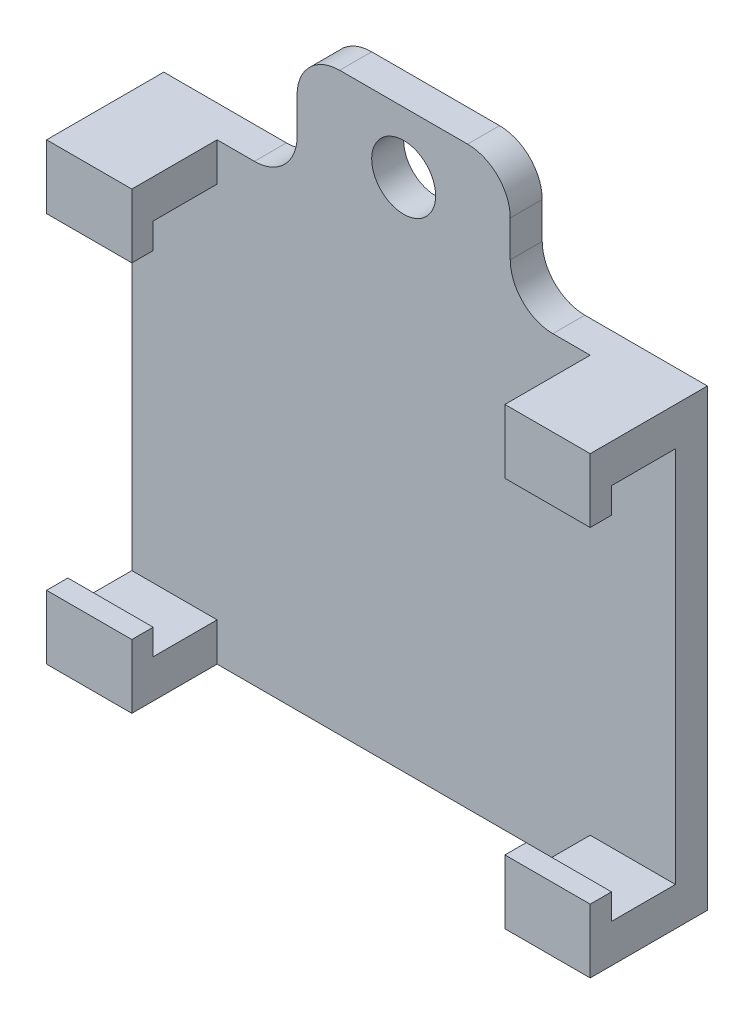
SolidWorks part; units mm, degrees
ref_plane "Front" through (0, 0, 0) normal (0, 0, 1) x (1, 0, 0)
ref_plane "Top" through (0, 0, 0) normal (0, 1, 0) x (1, 0, 0)
ref_plane "Right" through (0, 0, 0) normal (1, 0, 0) x (0, 0, -1)
sketch "Sketch1" plane through (0, 0, 0) normal (0, 1, 0) x (1, 0, 0)
  line L1 (0, 0) -> (25.5, 0)
  line L2 (0, 0) -> (0, 32.7)
  line L3 (0, 32.7) -> (25.5, 32.7)
  line L4 (25.5, 0) -> (25.5, 32.7)
  dimension "D1" = 25.5
  dimension "D2" = 32.7
extrude "Boss-Extrude1" add sketch "Sketch1" along normal blind 1.5
sketch "Sketch2" plane through (0, 1.5, 0) normal (0, 1, 0) x (1, 0, 0)
  line L0 (0, 32.7) -> (0, 0) construction
  line L1 (0, 24) -> (25.5, 24)
  line L2 (0, 24) -> (0, 27)
  line L3 (0, 27) -> (25.5, 27)
  line L4 (25.5, 24) -> (25.5, 27)
  line L5 (25.5, 0) -> (25.5, 32.7) construction
  line L7 (0, 8.7) -> (25.5, 8.7)
  line L8 (0, 8.7) -> (0, 5.7)
  line L9 (0, 5.7) -> (25.5, 5.7)
  line L10 (25.5, 8.7) -> (25.5, 5.7)
  line L11 (12.75, 8.7) -> (12.75, 24) construction
  point P14 (0, 16.35)
  point P15 (12.75, 16.35)
  dimension "D2" = 3
  dimension "D3" = 3
  dimension "D1" = 15.3
extrude "Boss-Extrude2" add sketch "Sketch2" along normal blind 4
sketch "Sketch3" plane through (0, 0, -24) normal (0, 0, 1) x (1, 0, 0)
  line L0 (25.5, 5.5) -> (25.5, 1.5) construction
  line L1 (0, 1.5) -> (25.5, 1.5)
  line L2 (0, 1.5) -> (0, 4.5)
  line L3 (0, 4.5) -> (25.5, 4.5)
  line L4 (25.5, 1.5) -> (25.5, 4.5)
  dimension "D1" = 3
extrude "Cut-Extrude1" cut sketch "Sketch3" against normal blind 1.2
sketch "Sketch4" plane through (0, 0, -8.7) normal (0, 0, -1) x (-1, 0, 0)
  line L0 (0, 5.5) -> (0, 1.5) construction
  line L1 (-25.5, 1.5) -> (0, 1.5)
  line L2 (-25.5, 1.5) -> (-25.5, 4.5)
  line L3 (-25.5, 4.5) -> (0, 4.5)
  line L4 (0, 1.5) -> (0, 4.5)
  dimension "D1" = 3
extrude "Cut-Extrude2" cut sketch "Sketch4" against normal blind 1.2
sketch "Sketch5" plane through (0, 1.5, 0) normal (0, 1, 0) x (1, 0, 0)
  line L0 (0, 32.7) -> (0, 27) construction
  line L1 (25.5, 32.7) -> (0, 32.7) construction
  line L2 (0, 5.7) -> (0, 0) construction
  circle A0 centre (12.75, 29.85) radius 1.5
  circle A1 centre (12.75, 2.85) radius 1.5
  point P6 (0, 29.85)
  point P9 (12.75, 32.7)
  point P12 (0, 2.85)
  dimension "D1" = 3
  dimension "D2" = 3
extrude "Cut-Extrude3" cut sketch "Sketch5" against normal through all
sketch "Sketch6" plane through (0, 0, 0) normal (0, -1, 0) x (1, 0, 0)
  line L0 (12.75, -29.85) -> (12.75, -5.7)
  line L1 (0, -5.7) -> (25.5, -5.7) construction
sketch "Sketch7" plane through (0, 0, 0) normal (0, 1, 0) x (1, 0, 0)
  line L1 (0, 5.7) -> (25.5, 5.7)
  line L2 (0, 5.7) -> (0, 0)
  line L3 (0, 0) -> (25.5, 0)
  line L4 (25.5, 5.7) -> (25.5, 0)
extrude "Cut-Extrude4" cut sketch "Sketch7" along normal through all
sketch "Sketch8" plane through (0, 0, -5.7) normal (0, 0, 1) x (1, 0, 0)
  line L0 (0, 5.5) -> (25.5, 5.5) construction
  line L1 (4, 5.5) -> (21.5, 5.5)
  line L2 (4, 5.5) -> (4, 1.5)
  line L3 (4, 1.5) -> (21.5, 1.5)
  line L4 (21.5, 5.5) -> (21.5, 1.5)
  line L5 (0, 1.5) -> (25.5, 1.5) construction
  line L6 (0, 1.5) -> (4, 1.5) construction
  line L16 (0, 5.5) -> (0, 0) construction
  point P8 (12.75, 5.5)
  point P9 (12.75, 5.5)
  dimension "D1" = 4
extrude "Cut-Extrude5" cut sketch "Sketch8" against normal through all
sketch "Sketch9" plane through (0, 1.5, 0) normal (0, 1, 0) x (1, 0, 0)
  line L0 (4, 27) -> (0, 27) construction
  line L1 (0, 32.7) -> (7.75, 32.7)
  line L2 (0, 32.7) -> (0, 27)
  line L3 (0, 27) -> (7.75, 27)
  line L4 (7.75, 32.7) -> (7.75, 27)
  line L5 (12.75, 32.7) -> (12.75, 5.7) construction
  line L6 (25.5, 32.7) -> (0, 32.7) construction
  line L7 (4, 5.7) -> (21.5, 5.7) construction
  line L8 (17.75, 32.7) -> (17.75, 27)
  line L9 (25.5, 27) -> (17.75, 27)
  line L10 (25.5, 32.7) -> (25.5, 27)
  line L11 (25.5, 32.7) -> (17.75, 32.7)
  dimension "D1" = 5
extrude "Cut-Extrude6" cut sketch "Sketch9" against normal through all
fillet "Fillet1" radius 2 4 edges at (7.75, 0.75, -27) (7.75, 0.75, -32.7) (17.75, 0.75, -32.7) (17.75, 0.75, -27)
move or copy body "Body-Move/Copy1" bodies to move or copy 109 copy no rotation origin (0, 2.75, -20.7) rotation axis (1, 0, 0) rotation angle 90
equation "\"Board Length\" = 17.7'The dimension of the board parallel with the clips"
equation "\"Board Width\"= 25.5'The dimension of the board perpendicular to the clips"
equation "\"D1@Sketch1\"=\"Board Width\""
equation "\"Board Slot Length\"= \"Board Length\" - 2 * \"Overhang Cut\""
equation "\"Overhang Cut\"= 1.2"
equation "\"D1@Cut-Extrude1\"=\"Overhang Cut\""
equation "\"D1@Sketch2\"=\"Board Slot Length\""
equation "\"Mount Length\"= \"Board Length\" + 7.5 * 2"
equation "\"D2@Sketch1\"=\"Mount Length\""
